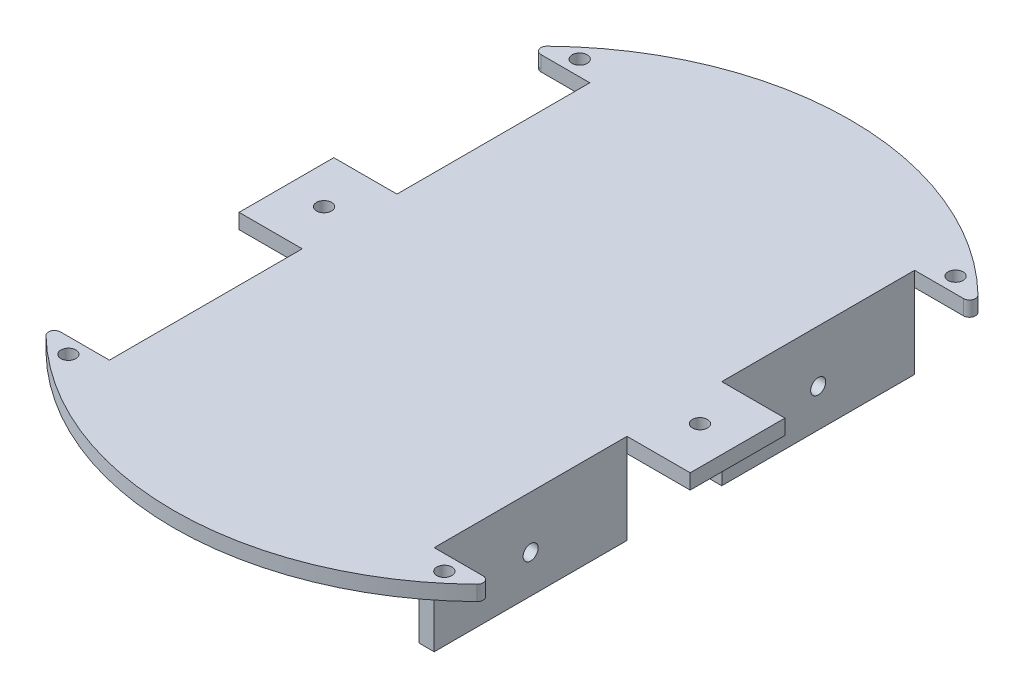
SolidWorks part; units mm, degrees
material "Alumina"
ref_plane "Front Plane" through (0, 0, 0) normal (0, 0, 1) x (1, 0, 0)
ref_plane "Top Plane" through (0, 0, 0) normal (0, 1, 0) x (1, 0, 0)
ref_plane "Right Plane" through (0, 0, 0) normal (1, 0, 0) x (0, 0, -1)
sketch "Sketch1" plane through (0, 0, 0) normal (0, 1, 0) x (1, 0, 0)
  line L0 (126.7418, 27.5057) -> (432.7418, 27.5057) construction
  line L5 (0, 112.5) -> (75, 112.5) construction
  line L6 (-75, 112.5) -> (0, 112.5) construction
  line L7 (-75, 112.5) -> (-75, 79.875) construction
  line L8 (-75, 0) -> (75, 0) construction
  line L9 (75, 112.5) -> (75, 79.875) construction
  line L10 (-75, 112.5) -> (75, 0) construction
  line L11 (-75, 0) -> (75, 112.5) construction
  line L12 (-75, 15.75) -> (-75, -15.75)
  line L13 (75, 15.75) -> (75, 0)
  line L14 (-75, 0) -> (75, 0) construction
  line L15 (0, -56.25) -> (0, 56.25) construction
  line L16 (54, 79.875) -> (54, 15.75)
  line L17 (54, 15.75) -> (75, 15.75)
  line L18 (-75, 0) -> (75, -112.5) construction
  line L19 (-75, -112.5) -> (75, 0) construction
  line L20 (75, -112.5) -> (75, -79.875) construction
  line L21 (-75, -112.5) -> (-75, -79.875) construction
  line L22 (-75, -112.5) -> (0, -112.5) construction
  line L23 (0, -112.5) -> (75, -112.5) construction
  line L24 (-54, -79.875) -> (-70.252, -79.875)
  line L25 (54, 79.875) -> (70.252, 79.875)
  line L26 (-75, 15.75) -> (-75, -15.75)
  line L27 (-54, 15.75) -> (-75, 15.75)
  line L28 (-54, 79.875) -> (-54, 15.75)
  line L29 (-54, 79.875) -> (-70.252, 79.875)
  line L30 (-54, -79.875) -> (-54, -15.75)
  line L31 (-54, -15.75) -> (-75, -15.75)
  line L32 (54, -79.875) -> (70.252, -79.875)
  line L33 (54, -15.75) -> (75, -15.75)
  line L34 (54, -79.875) -> (54, -15.75)
  line L35 (75, -15.75) -> (75, 0)
  arc A1 (71.6498, 83.3055) -> (-71.6498, 83.3055) centre (0, 9.9806) ccw
  arc A2 (71.6498, -83.3055) -> (-71.6498, -83.3055) centre (0, -9.9806) cw
  arc A3 (-70.252, -79.875) -> (-71.6498, -83.3055) centre (-70.252, -81.875) ccw
  arc A4 (70.252, -79.875) -> (71.6498, -83.3055) centre (70.252, -81.875) cw
  arc A5 (71.6498, 83.3055) -> (70.252, 79.875) centre (70.252, 81.875) cw
  arc A6 (-71.6498, 83.3055) -> (-70.252, 79.875) centre (-70.252, 81.875) ccw
  point P0 (0, 56.25)
  point P16 (0, 0)
  point P18 (0, 0)
  point P35 (0, -56.25)
  dimension "D3" = 64.125
  dimension "D5" = 2
  dimension "D1" = 112.5
  dimension "D2" = 150
  dimension "D4" = 15.75
extrude "Boss-Extrude1" add sketch "Sketch1" along normal blind 5 contours A2 L32 L34 L33 L35 L13 L17 L16 L25 A1 L29 L28 L27 L12 L31 L30 L24
sketch "Sketch2" plane through (0, 0, 0) normal (0, -1, 0) x (1, 0, 0)
  line L0 (54, 79.875) -> (-54, 79.875) construction
  line L1 (54, 79.875) -> (49, 79.875)
  line L2 (54, 79.875) -> (54, 15.75)
  line L3 (54, 15.75) -> (49, 15.75)
  line L4 (49, 79.875) -> (49, 15.75)
  line L5 (54, 79.875) -> (54, -15.75) construction
  line L6 (-49, 79.875) -> (-49, 15.75)
  line L7 (-49, 79.875) -> (-54, 79.875)
  line L8 (-54, 79.875) -> (-54, 15.75)
  line L9 (-49, 15.75) -> (-54, 15.75)
  line L10 (-49, -15.75) -> (-49, -79.875)
  line L11 (-49, -15.75) -> (-54, -15.75)
  line L12 (-54, -15.75) -> (-54, -79.875)
  line L13 (-49, -79.875) -> (-54, -79.875)
  line L14 (54, -15.75) -> (54, -79.875)
  line L15 (54, -15.75) -> (49, -15.75)
  line L16 (49, -15.75) -> (49, -79.875)
  line L17 (54, -79.875) -> (49, -79.875)
  line L18 (-54, 79.875) -> (-54, 15.75) construction
  line L19 (-54, -79.875) -> (-54, -15.75) construction
  line L20 (-54, -15.75) -> (-75, -15.75) construction
  dimension "D1" = 5
  dimension "D2" = 2
  dimension "D3" = 2
extrude "Boss-Extrude2" add sketch "Sketch2" along normal blind 25
sketch "Sketch3" plane through (54, 0, 0) normal (1, 0, 0) x (0, 0, -1)
  line L0 (-79.875, 5) -> (-15.75, -25) construction
  line L1 (79.875, -25) -> (15.75, 5) construction
  line L2 (-79.875, 5) -> (-15.75, 5) construction
  line L3 (-79.875, 5) -> (-79.875, 0) construction
  line L4 (-15.75, -25) -> (-79.875, 0.28) construction
  line L5 (-79.875, -25) -> (-79.875, 0) construction
  line L6 (79.875, -25) -> (15.75, 0.28) construction
  line L7 (15.75, -25) -> (15.75, 0) construction
  circle A0 centre (-47.8125, -12.36) radius 2.5
  circle A2 centre (47.8125, -12.36) radius 2.5
  point P10 (47.8125, -12.36)
  point P12 (-47.8125, -12.36)
  point P13 (47.8125, -10)
  point P22 (-47.8125, -10)
  dimension "D1" = 5
  dimension "D2" = 2.36
  dimension "D3" = 2.36
extrude "Cut-Extrude1" cut sketch "Sketch3" against normal through all both and the other way through all
sketch "Sketch4" plane through (0, 5, 0) normal (0, 1, 0) x (1, 0, 0)
  line L1 (-62.5, -85) -> (62.5, -85) construction
  line L2 (-62.5, -85) -> (-62.5, 85) construction
  line L3 (-62.5, 85) -> (62.5, 85) construction
  line L4 (62.5, -85) -> (62.5, 85) construction
  line L5 (-62.5, -85) -> (62.5, 85) construction
  line L6 (-62.5, 85) -> (62.5, -85) construction
  circle A1 centre (-62.5, 85) radius 2.5
  circle A2 centre (62.5, 85) radius 2.5
  circle A3 centre (62.5, 0) radius 2.5
  circle A4 centre (62.5, -85) radius 2.5
  circle A5 centre (-62.5, 0) radius 2.5
  circle A6 centre (-62.5, -85) radius 2.5
  point P0 (0, 0)
  dimension "D3" = 5
  dimension "D1" = 125
  dimension "D2" = 170
  dimension "D4" = 2
  dimension "D5" = 3
extrude "Cut-Extrude2" cut sketch "Sketch4" against normal through all both
